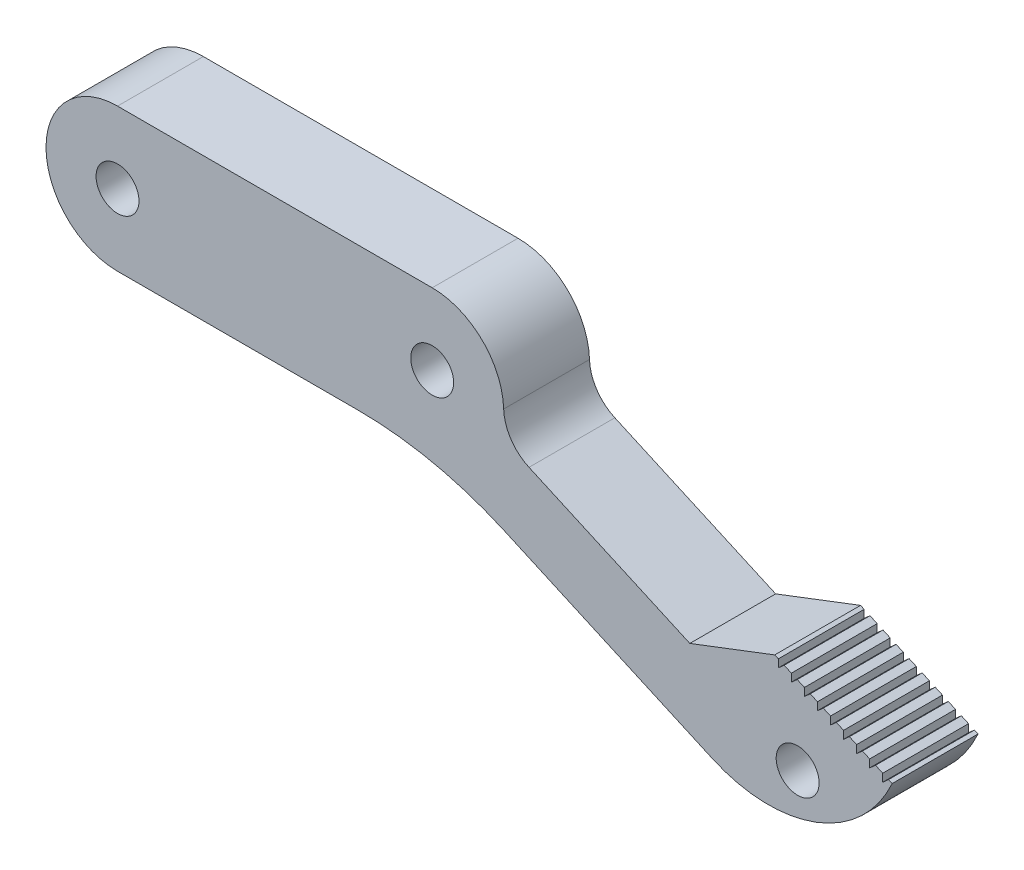
SolidWorks part; units mm, degrees
material "普通碳钢"
ref_plane "前视" through (0, 0, 0) normal (0, 0, 1) x (1, 0, 0)
ref_plane "上视" through (0, 0, 0) normal (0, 1, 0) x (1, 0, 0)
ref_plane "右视" through (0, 0, 0) normal (1, 0, 0) x (0, 0, -1)
sketch "草图1" plane through (0, 0, 0) normal (0, 0, 1) x (1, 0, 0)
  line L0 (-11, 0) -> (11, 0) construction
  line L1 (-11, 5) -> (11, 5)
  line L2 (-11, -5) -> (11, -5)
  arc A0 (-11, 5) -> (-11, -5) centre (-11, 0) ccw
  arc A1 (11, -5) -> (11, 5) centre (11, 0) ccw
  circle A2 centre (-11, 0) radius 1.5
  circle A3 centre (11, 0) radius 1.5
  point P2 (0, 0)
  dimension "D3" = 3
  dimension "D1" = 10
  dimension "D2" = 22
extrude "凸台-拉伸1" add sketch "草图1" along normal blind 6 contours L1 A1 L2 A0 | A2 | A3
sketch "草图2" plane through (0, 0, 6) normal (0, 0, 1) x (1, 0, 0)
  line L0 (17.7688, -2.4866) -> (29.0116, -7.527)
  line L1 (30.6027, -13.7199) -> (16.0324, -7.1877)
  line L2 (-11, -5) -> (11, -5) construction
  line L3 (29.0116, -7.527) -> (34.9453, -5.2557)
  line L4 (34.9453, -5.2557) -> (43.1577, -8.9375)
  line L5 (11, 0) -> (36.5498, -11.4545) construction
  line L6 (5.8051, -5) -> (11, -5)
  line L7 (43.1577, -8.9375) -> (32.6654, -32.341) construction
  line L8 (43.1577, -8.9375) -> (-17.0434, 18.052) construction
  line L9 (0.4545, 25.5498) -> (-11, 0) construction
  arc A0 (11, -5) -> (11, 5) centre (11, 0) ccw construction
  arc A1 (16.0324, -7.1877) -> (5.8051, -5) centre (5.8051, -30) ccw
  arc A2 (11, -5) -> (15.9975, 0.1568) centre (11, 0) ccw
  arc A3 (43.1577, -8.9375) -> (30.6027, -13.7199) centre (34.4891, -5.0512) cw
  circle A4 centre (36.5498, -11.4545) radius 1.5
  circle A5 centre (-11, 0) radius 1.5 construction
  circle A6 centre (0.4545, 25.5498) radius 1.5 construction
  arc A8 (17.7688, -2.4866) -> (15.9975, 0.1568) centre (18.9961, 0.2508) cw
  dimension "D2" = 3
  dimension "D5" = 9
  dimension "D6" = 8.5
  dimension "D8" = 28
  dimension "D9" = 3
  dimension "D10" = 25
  dimension "D11" = 3
  dimension "D1" = 5
  dimension "D3" = 28
  dimension "D4" = 9.5
  dimension "D7" = 33
extrude "凸台-拉伸2" add sketch "草图2" against normal blind 6
sketch "草图3" plane through (0, 0, 6) normal (0, 0, 1) x (1, 0, 0)
  line L0 (42.497, -9.1892) -> (35.8024, -6.1879) construction
  line L1 (43.1577, -8.9375) -> (34.9453, -5.2557) construction
  line L2 (42.906, -8.8247) -> (42.497, -9.1892)
  line L3 (42.497, -9.1892) -> (42.497, -8.6413)
  line L4 (42.906, -8.8247) -> (42.497, -8.6413) construction
  line L5 (42.7015, -8.733) -> (42.497, -9.1892) construction
  line L6 (42.906, -8.8247) -> (42.497, -8.6413)
  dimension "D1" = 0.5
  dimension "D2" = 0.5
extrude "切除-拉伸1" cut sketch "草图3" against normal blind 6
pattern_linear "阵列(线性)1" count 9 spacing 1 along (-0.9125, 0.4091, 0) of "切除-拉伸1"
